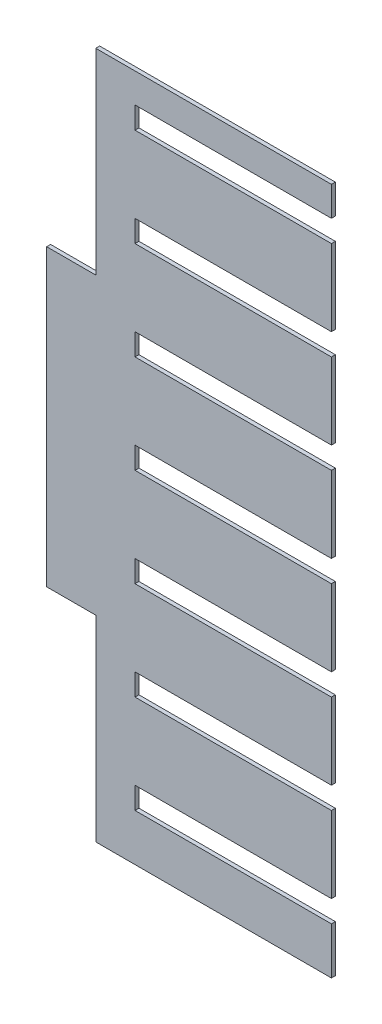
SolidWorks part; units mm, degrees
material "Rubber"
ref_plane "Front Plane" through (0, 0, 0) normal (0, 0, 1) x (1, 0, 0)
ref_plane "Top Plane" through (0, 0, 0) normal (0, 1, 0) x (1, 0, 0)
ref_plane "Right Plane" through (0, 0, 0) normal (1, 0, 0) x (0, 0, -1)
sketch "Sketch1" plane through (0, 0, 0) normal (0, 0, 1) x (1, 0, 0)
  line L8 (-15, -175) -> (-15, 175)
  line L9 (-15, 175) -> (-150, 175)
  line L10 (-150, 175) -> (-150, 75)
  line L11 (-150, 75) -> (-175, 75)
  line L12 (-175, 75) -> (-175, -75)
  line L13 (-175, -75) -> (-150, -75)
  line L14 (-150, -75) -> (-150, -175)
  line L15 (-150, -175) -> (-15, -175)
  line L16 (-15, -175) -> (-15, 175)
  line L17 (-15, 175) -> (-150, 175)
  line L18 (-150, 175) -> (-150, 75)
  line L19 (-150, 75) -> (-175, 75)
  line L20 (-175, 75) -> (-175, -75)
  line L21 (-175, -75) -> (-150, -75)
  line L22 (-150, -75) -> (-150, -175)
  line L23 (-150, -175) -> (-15, -175)
  dimension "D1" = 0
extrude "Boss-Extrude1" add sketch "Sketch1" along normal blind 2
sketch "Sketch2" plane through (0, 0, 2) normal (0, 0, 1) x (1, 0, 0)
  line L0 (-130, 160) -> (-30, 160) construction
  line L1 (-130, 160) -> (-30, 160)
  line L2 (-130, 148.8761) -> (-130, 160) construction
  line L3 (-30, 148.8761) -> (-130, 148.8761) construction
  line L4 (-30, 160) -> (-30, 148.8761) construction
  line L5 (-130, 148.8761) -> (-130, 160)
  line L6 (-30, 148.8761) -> (-130, 148.8761)
  line L7 (-30, 160) -> (-30, 148.8761)
extrude "Cut-Extrude1" cut sketch "Sketch2" against normal blind 2
pattern_linear "LPattern1" count 7 spacing 50 along (0, -1, 0) of "Cut-Extrude1"
sketch "Sketch4" plane through (0, 0, 2) normal (0, 0, 1) x (1, 0, 0)
  line L0 (-150, -175) -> (-15, -175) construction
  line L1 (-15, 175) -> (-30, 175)
  line L2 (-15, 175) -> (-15, -175)
  line L3 (-15, -175) -> (-30, -175)
  line L4 (-30, 175) -> (-30, -175)
  line L5 (-30, -1.1239) -> (-30, 10) construction
extrude "Cut-Extrude2" cut sketch "Sketch4" against normal up to next
